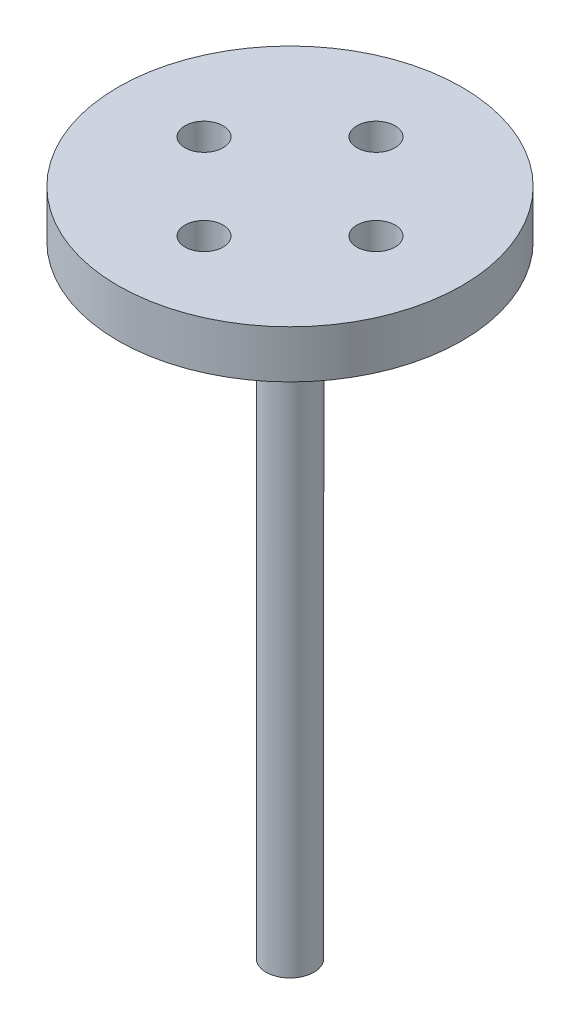
SolidWorks part; units mm, degrees
ref_plane "前视基准面" through (0, 0, 0) normal (0, 0, 1) x (1, 0, 0)
ref_plane "上视基准面" through (0, 0, 0) normal (0, 1, 0) x (1, 0, 0)
ref_plane "右视基准面" through (0, 0, 0) normal (1, 0, 0) x (0, 0, -1)
sketch "草图1" plane through (0, 0, 0) normal (0, 1, 0) x (1, 0, 0)
  circle A0 centre (0, 0) radius 18
  circle A1 centre (0, 0) radius 9 construction
  circle A2 centre (0, 9) radius 2
  circle A3 centre (9, 0) radius 2
  circle A4 centre (-9, 0) radius 2
  circle A5 centre (0, -9) radius 2
  dimension "D1" = 36
  dimension "D2" = 18
  dimension "D3" = 4
  dimension "D4" = 4
  dimension "D5" = 4
  dimension "D6" = 4
extrude "凸台-拉伸1" add sketch "草图1" along normal blind 5
sketch "草图2" plane through (0, 0, 0) normal (0, -1, 0) x (1, 0, 0)
  circle A0 centre (0, 0) radius 2.5
  dimension "D1" = 5
extrude "凸台-拉伸2" add sketch "草图2" along normal blind 65
